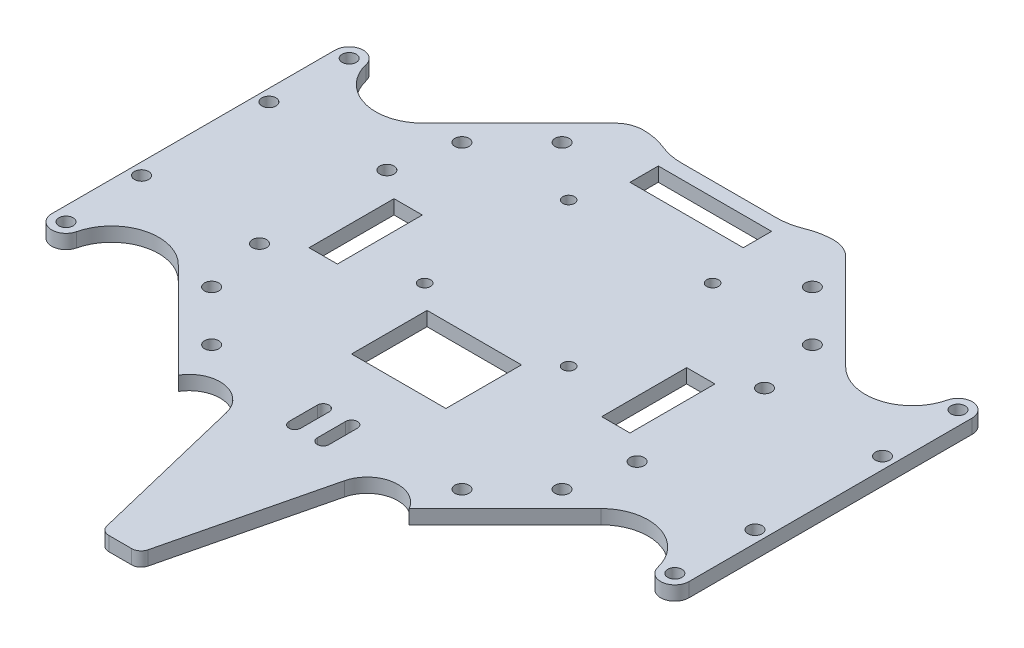
SolidWorks part; units mm, degrees
ref_plane "前视基准面" through (0, 0, 0) normal (0, 0, 1) x (1, 0, 0)
ref_plane "上视基准面" through (0, 0, 0) normal (0, 1, 0) x (1, 0, 0)
ref_plane "右视基准面" through (0, 0, 0) normal (1, 0, 0) x (0, 0, -1)
sketch "草图1" plane through (0, 0, 0) normal (0, 1, 0) x (1, 0, 0)
  line L0 (0, 79.9225) -> (0, -68.1747) construction
  line L1 (-93.1075, 0) -> (111.4791, 0) construction
  line L2 (-55.8728, 55.8728) -> (39.2533, -39.2533) construction
  line L3 (-19.318, 44.3216) -> (-45.661, 17.9787) construction
  line L4 (-12.5, -50) -> (-12.5, -81)
  line L5 (-67.5, 48) -> (67.5, 48)
  line L6 (-67.5, 48) -> (-67.5, -48)
  line L7 (-67.5, -48) -> (-14.5, -48)
  line L8 (67.5, 48) -> (67.5, -48)
  line L9 (-67.5, 48) -> (67.5, -48) construction
  line L10 (-67.5, -48) -> (67.5, 48) construction
  line L11 (-10.5, -83) -> (10.5, -83)
  line L12 (12.5, -81) -> (12.5, -50)
  line L13 (14.5, -48) -> (67.5, -48)
  circle A0 centre (-37.1231, 26.5165) radius 1.5
  circle A1 centre (-26.5165, 37.1231) radius 1.5
  circle A2 centre (26.5165, 37.1231) radius 1.5
  circle A3 centre (37.1231, 26.5165) radius 1.5
  circle A4 centre (37.1231, -26.5165) radius 1.5
  circle A5 centre (26.5165, -37.1231) radius 1.5
  circle A6 centre (-37.1231, -26.5165) radius 1.5
  circle A7 centre (-26.5165, -37.1231) radius 1.5
  arc A8 (-12.5, -50) -> (-14.5, -48) centre (-14.5, -50) ccw
  arc A9 (10.5, -83) -> (12.5, -81) centre (10.5, -81) ccw
  arc A10 (-12.5, -81) -> (-10.5, -83) centre (-10.5, -81) ccw
  arc A11 (14.5, -48) -> (12.5, -50) centre (14.5, -50) ccw
  point P25 (0, 0)
  point P38 (12.5, -83)
  point P41 (-12.5, -83)
  point P44 (12.5, -48)
  dimension "D3" = 3
  dimension "D11" = 2
  dimension "D12" = 2
  dimension "D1" = 45
  dimension "D2" = 45
  dimension "D4" = 15
  dimension "D5" = 7.5
  dimension "D6" = 135
  dimension "D7" = 96
  dimension "D8" = 25
  dimension "D9" = 12.5
  dimension "D10" = 35
extrude "凸台-拉伸1" add sketch "草图1" along normal blind 3
sketch "草图2" plane through (0, 3, 0) normal (0, 1, 0) x (1, 0, 0)
  line L0 (0, 63.5592) -> (0, -64.9484) construction
  line L1 (-71.5475, 0) -> (75.0978, 0) construction
  line L2 (-37.1231, -26.5165) -> (-26.5165, -37.1231) construction
  line L3 (-33.234, -15.5563) -> (-15.5563, -33.234) construction
  line L4 (-26.5481, -26.5481) -> (-35.1226, -35.1226) construction
  line L5 (-33.234, -15.5563) -> (-43.6511, -25.9734) construction
  line L6 (-15.25, 3.25) -> (15.25, -27.25) construction
  line L7 (15.25, 3.25) -> (-15.25, -27.25) construction
  line L8 (3, 43) -> (3, 37) construction
  line L9 (-17.5, 5.5) -> (17.5, 5.5) construction
  line L10 (-17.5, 5.5) -> (-17.5, -29.5) construction
  line L11 (-17.5, -29.5) -> (17.5, -29.5) construction
  line L12 (17.5, 5.5) -> (17.5, -29.5) construction
  line L13 (-17.5, 5.5) -> (17.5, -29.5) construction
  line L14 (-17.5, -29.5) -> (17.5, 5.5) construction
  line L15 (4.25, 43) -> (4.25, 37) construction
  line L16 (1.75, 43) -> (1.75, 37) construction
  line L17 (-3, 43) -> (-3, 37) construction
  line L18 (-4.25, 43) -> (-4.25, 37) construction
  line L19 (-1.75, 43) -> (-1.75, 37) construction
  line L20 (3, -43) -> (3, -37) construction
  line L21 (4.25, -43) -> (4.25, -37)
  line L22 (1.75, -43) -> (1.75, -37)
  line L23 (-3, -43) -> (-3, -37) construction
  line L24 (-4.25, -43) -> (-4.25, -37)
  line L25 (-1.75, -43) -> (-1.75, -37)
  line L27 (-10, -8) -> (10, -8)
  line L28 (-10, -8) -> (-10, -24)
  line L29 (-10, -24) -> (10, -24)
  line L30 (10, -8) -> (10, -24)
  line L31 (-10, -8) -> (10, -24) construction
  line L32 (-10, -24) -> (10, -8) construction
  circle A0 centre (-40, 13.5) radius 1.5
  circle A1 centre (-40, -13.5) radius 1.5
  circle A3 centre (-15.25, 3.25) radius 1.25 construction
  circle A4 centre (15.25, 3.25) radius 1.25 construction
  circle A5 centre (15.25, -27.25) radius 1.25 construction
  circle A6 centre (-15.25, -27.25) radius 1.25 construction
  circle A7 centre (-65, 13.5) radius 1.5
  circle A8 centre (-65, -13.5) radius 1.5
  circle A13 centre (40, -13.5) radius 1.5
  circle A14 centre (40, 13.5) radius 1.5
  arc A15 (4.25, 43) -> (1.75, 43) centre (3, 43) ccw construction
  arc A16 (1.75, 37) -> (4.25, 37) centre (3, 37) ccw construction
  arc A17 (-4.25, 43) -> (-1.75, 43) centre (-3, 43) cw construction
  arc A18 (-1.75, 37) -> (-4.25, 37) centre (-3, 37) cw construction
  circle A19 centre (65, -13.5) radius 1.5
  circle A20 centre (65, 13.5) radius 1.5
  arc A21 (4.25, -43) -> (1.75, -43) centre (3, -43) cw
  arc A22 (1.75, -37) -> (4.25, -37) centre (3, -37) cw
  arc A23 (-4.25, -43) -> (-1.75, -43) centre (-3, -43) ccw
  arc A24 (-1.75, -37) -> (-4.25, -37) centre (-3, -37) ccw
  circle A25 centre (-15.25, 27.25) radius 1.25
  circle A26 centre (15.25, 27.25) radius 1.25
  circle A27 centre (15.25, -3.25) radius 1.25
  circle A28 centre (-15.25, -3.25) radius 1.25
  point P27 (0, -12)
  point P41 (3, 40)
  point P48 (-3, 40)
  point P57 (3, -40)
  point P66 (-3, -40)
  point P81 (0, -16)
  dimension "D1" = 3
  dimension "D6" = 2.5
  dimension "D19" = 2.5
  dimension "D20" = 6
  dimension "D21" = 40
  dimension "D24" = 3
  dimension "D2" = 27
  dimension "D3" = 13.5
  dimension "D4" = 25
  dimension "D5" = 25
  dimension "D7" = 30.5
  dimension "D8" = 30.5
  dimension "D9" = 15.25
  dimension "D10" = 30.5
  dimension "D11" = 10.5
  dimension "D12" = 25
  dimension "D13" = 7.5
  dimension "D14" = 12.5
  dimension "D15" = 40
  dimension "D16" = 35
  dimension "D17" = 35
  dimension "D18" = 12
  dimension "D22" = 3
  dimension "D23" = 27
  dimension "D25" = 16
  dimension "D26" = 20
  dimension "D27" = 16
extrude "切除-拉伸1" cut sketch "草图2" against normal blind 31
sketch "草图3" plane through (0, 3, 0) normal (0, 1, 0) x (1, 0, 0)
  line L0 (0, 0) -> (-95.846, 0) construction
  line L1 (0, 0) -> (0, 65.2529) construction
  line L2 (-67.5, 16.5) -> (-37.5, 16.5) construction
  line L3 (-37.5, 16.5) -> (-37.5, -16.5) construction
  line L4 (-37.5, -16.5) -> (-67.5, -16.5) construction
  line L5 (-67.5, -16.5) -> (-67.5, 16.5) construction
  line L6 (67.5, 48) -> (-67.5, 48) construction
  line L7 (-12, 43) -> (12, 43)
  line L8 (-12, 43) -> (-12, 37)
  line L9 (-12, 37) -> (12, 37)
  line L10 (12, 43) -> (12, 37)
  line L11 (-12, 43) -> (12, 37) construction
  line L12 (-12, 37) -> (12, 43) construction
  line L17 (34, -9) -> (28, -9)
  line L18 (-34, 9) -> (-28, 9)
  line L19 (-34, 9) -> (-34, -9)
  line L20 (-34, -9) -> (-28, -9)
  line L21 (-28, 9) -> (-28, -9)
  line L22 (-34, 9) -> (-28, -9) construction
  line L23 (-34, -9) -> (-28, 9) construction
  line L24 (28, 9) -> (28, -9)
  line L25 (34, 9) -> (34, -9)
  line L26 (34, 9) -> (28, 9)
  circle A0 centre (-40, 13.5) radius 1.5 construction
  circle A1 centre (-65, 13.5) radius 1.5 construction
  point P12 (0, 40)
  point P23 (-31, 0)
  dimension "D4" = 40
  dimension "D5" = 65
  dimension "D1" = 30
  dimension "D2" = 33
  dimension "D3" = 16.5
  dimension "D6" = 37.5
  dimension "D7" = 6
  dimension "D8" = 5
  dimension "D9" = 24
  dimension "D10" = 31
  dimension "D11" = 6
  dimension "D12" = 18
extrude "切除-拉伸2" cut sketch "草图3" against normal blind 10
sketch "草图5" plane through (0, 3, 0) normal (0, 1, 0) x (1, 0, 0)
  line L0 (-26.5165, 37.1231) -> (-37.1231, 26.5165) construction
  line L1 (-24.468, 46.2426) -> (-44.7802, 25.9305)
  line L2 (67.5, 48) -> (-67.5, 48) construction
  line L3 (0, 0) -> (0, 54.7575) construction
  line L4 (0, 0) -> (70.8766, 0) construction
  line L5 (-67.5, 48) -> (-67.5, -48) construction
  line L6 (67.5, 48) -> (-20.2254, 48) construction
  line L7 (-20.2254, 48) -> (-67.5, 48)
  line L8 (-67.5, 48) -> (-67.5, 30)
  line L9 (67.5, 48) -> (67.5, 30)
  line L10 (24.468, 46.2426) -> (44.7802, 25.9305)
  line L11 (20.2254, 48) -> (67.5, 48)
  line L12 (67.5, -48) -> (67.5, -30)
  line L13 (20.2254, -48) -> (67.5, -48)
  line L14 (24.468, -46.2426) -> (44.7802, -25.9305)
  line L15 (-20.2254, -48) -> (-67.5, -48)
  line L16 (-67.5, -48) -> (-67.5, -30)
  line L17 (-24.468, -46.2426) -> (-44.7802, -25.9305)
  circle A0 centre (-26.5165, 37.1231) radius 1.5 construction
  circle A1 centre (-64.5, 30) radius 1.5
  circle A2 centre (-64.5, -30) radius 1.5 construction
  circle A3 centre (-64.5, 30) radius 3 construction
  arc A4 (-61.5811, 30.6927) -> (-44.7802, 25.9305) centre (-51.8513, 33.0016) ccw
  arc A5 (-20.2254, 48) -> (-24.468, 46.2426) centre (-20.2254, 42) ccw
  arc A6 (-67.5, 30) -> (-61.5811, 30.6927) centre (-64.5, 30) cw
  circle A7 centre (64.5, 30) radius 1.5
  arc A8 (61.5811, 30.6927) -> (44.7802, 25.9305) centre (51.8513, 33.0016) cw
  arc A9 (67.5, 30) -> (61.5811, 30.6927) centre (64.5, 30) ccw
  arc A10 (20.2254, 48) -> (24.468, 46.2426) centre (20.2254, 42) cw
  circle A11 centre (64.5, -30) radius 1.5
  arc A12 (20.2254, -48) -> (24.468, -46.2426) centre (20.2254, -42) ccw
  arc A13 (61.5811, -30.6927) -> (44.7802, -25.9305) centre (51.8513, -33.0016) ccw
  arc A14 (67.5, -30) -> (61.5811, -30.6927) centre (64.5, -30) cw
  circle A15 centre (-64.5, -30) radius 1.5
  arc A16 (-67.5, -30) -> (-61.5811, -30.6927) centre (-64.5, -30) ccw
  arc A17 (-61.5811, -30.6927) -> (-44.7802, -25.9305) centre (-51.8513, -33.0016) cw
  arc A18 (-20.2254, -48) -> (-24.468, -46.2426) centre (-20.2254, -42) cw
  dimension "D2" = 3
  dimension "D6" = 6
  dimension "D7" = 10
  dimension "D8" = 6
  dimension "D1" = 5
  dimension "D3" = 3
  dimension "D5" = 30
extrude "切除-拉伸3" cut sketch "草图5" against normal blind 10
sketch "草图6" plane through (0, 3, 0) normal (0, 1, 0) x (1, 0, 0)
  line L0 (-10, 46) -> (10, 46)
  line L1 (0, 0) -> (0, 60.9736) construction
  line L2 (20.2254, 48) -> (-20.2254, 48) construction
  line L3 (20.2254, 48) -> (-20.2254, 48) construction
  line L4 (-20.2254, 48) -> (20.2254, 48) construction
  line L5 (-20.2254, 48) -> (-20.2254, 49)
  line L6 (-20.2254, 49) -> (20.2254, 49)
  line L7 (20.2254, 49) -> (20.2254, 48)
  line L10 (0, 0) -> (0, -99.7402) construction
  line L15 (-4.3711, -81.472) -> (-12.5, -48)
  line L18 (-2.4276, -83) -> (2.4276, -83)
  line L19 (-10.5, -83) -> (10.5, -83) construction
  line L21 (-24.468, -84) -> (24.468, -84)
  line L22 (4.3711, -81.472) -> (12.5, -48)
  line L23 (12.5, -81) -> (12.5, -50) construction
  line L24 (14.5, -48) -> (20.2254, -48) construction
  line L25 (-24.468, -46.2426) -> (-24.468, -84)
  line L26 (24.468, -46.2426) -> (24.468, -84)
  arc A0 (-20.2254, 48) -> (-24.468, 46.2426) centre (-20.2254, 42) ccw construction
  arc A1 (-20.2254, 48) -> (-24.468, 46.2426) centre (-20.2254, 42) ccw construction
  arc A2 (-20.2254, 48) -> (-15, 46.978) centre (-20.2254, 34.131) cw
  arc A3 (-15, 46.978) -> (-10, 46) centre (-10, 59.2707) ccw
  arc A4 (15, 46.978) -> (10, 46) centre (10, 59.2707) cw
  arc A5 (20.2254, 48) -> (15, 46.978) centre (20.2254, 34.131) ccw
  arc A9 (20.2254, -48) -> (24.468, -46.2426) centre (20.2254, -42) ccw construction
  arc A10 (20.2254, -48) -> (24.468, -46.2426) centre (20.2254, -42) ccw construction
  arc A13 (-24.468, -46.2426) -> (-20.2254, -48) centre (-20.2254, -42) ccw construction
  arc A14 (-24.468, -46.2426) -> (-20.2254, -48) centre (-20.2254, -42) ccw construction
  arc A15 (-4.3711, -81.472) -> (-2.4276, -83) centre (-2.4276, -81) ccw
  arc A16 (2.4276, -83) -> (4.3711, -81.472) centre (2.4276, -81) ccw
  arc A17 (12.5, -48) -> (24.468, -46.2426) centre (18.8391, -49.5395) cw
  arc A18 (-12.5, -48) -> (-24.468, -46.2426) centre (-18.8391, -49.5395) ccw
  point P40 (-4, -83)
  point P43 (4, -83)
  dimension "D6" = 2
  dimension "D7" = 2
  dimension "D1" = 20
  dimension "D2" = 1
  dimension "D3" = 2
  dimension "D4" = 5
  dimension "D5" = 8
  dimension "D8" = 1
extrude "切除-拉伸4" cut sketch "草图6" against normal blind 3
